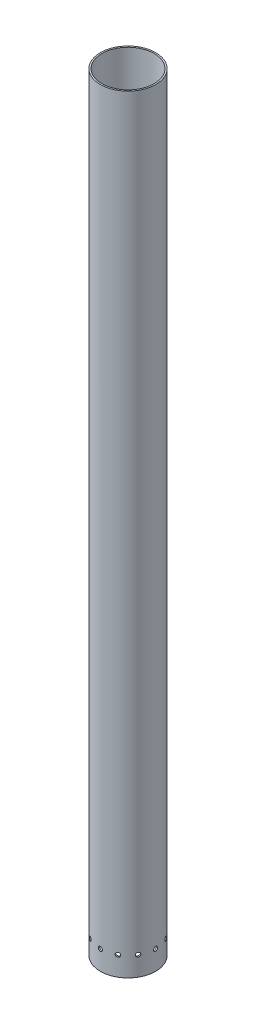
SolidWorks part; units mm, degrees
material "6063-T6"
ref_plane "Front Plane" through (0, 0, 0) normal (0, 0, 1) x (1, 0, 0)
ref_plane "Top Plane" through (0, 0, 0) normal (0, 1, 0) x (1, 0, 0)
ref_plane "Right Plane" through (0, 0, 0) normal (1, 0, 0) x (0, 0, -1)
sketch "Sketch1" plane through (0, 0, 0) normal (0, 0, 1) x (1, 0, 0)
  line L0 (0, 0) -> (0, 45.6531) construction
  line L1 (25.5143, 29.9858) -> (26.9875, 29.9858)
  line L2 (25.5143, 29.9858) -> (25.5143, -719.3142)
  line L3 (25.5143, -719.3142) -> (26.9875, -719.3142)
  line L4 (26.9875, 29.9858) -> (26.9875, -719.3142)
revolve "Revolve1" add sketch "Sketch1" angle 360 about L0
ref_plane "Plane1" through (0, 0, -26.9875) normal (0, 0, -1) x (-1, 0, 0)
sketch "Sketch2" plane through (0, 0, -26.9875) normal (0, 0, -1) x (-1, 0, 0)
  point P0 (0, -700.2642)
hole_wizard "#10-32 Tapped Hole1" positions "Sketch2" profile "Sketch3" tap size "#10-32" standard "ANSI Inch"
sketch "Sketch3" plane through (0, -700.2642, -26.9875) normal (1, 0, 0) x (0, 1, 0)
  line L0 (0, 0) -> (0, 15.1833)
  line L1 (0, 15.1833) -> (2.0193, 13.97)
  line L2 (2.0193, 13.97) -> (2.0193, 0)
  line L5 (2.0193, 0) -> (0, 0)
  line L10 (0, 15.1833) -> (-2.0193, 13.97) construction
  line L11 (0, -6.35) -> (0, 107.95) construction
  dimension "Tap Drill Dia." = 4.0386
  dimension "Tap Drill Depth" = 13.97
  dimension "Drill Angle" = 118
pattern_circular "CirPattern1" count 12 over 360 about axis through (0, 0, 0) along (0, -1, 0) of "#10-32 Tapped Hole1"
